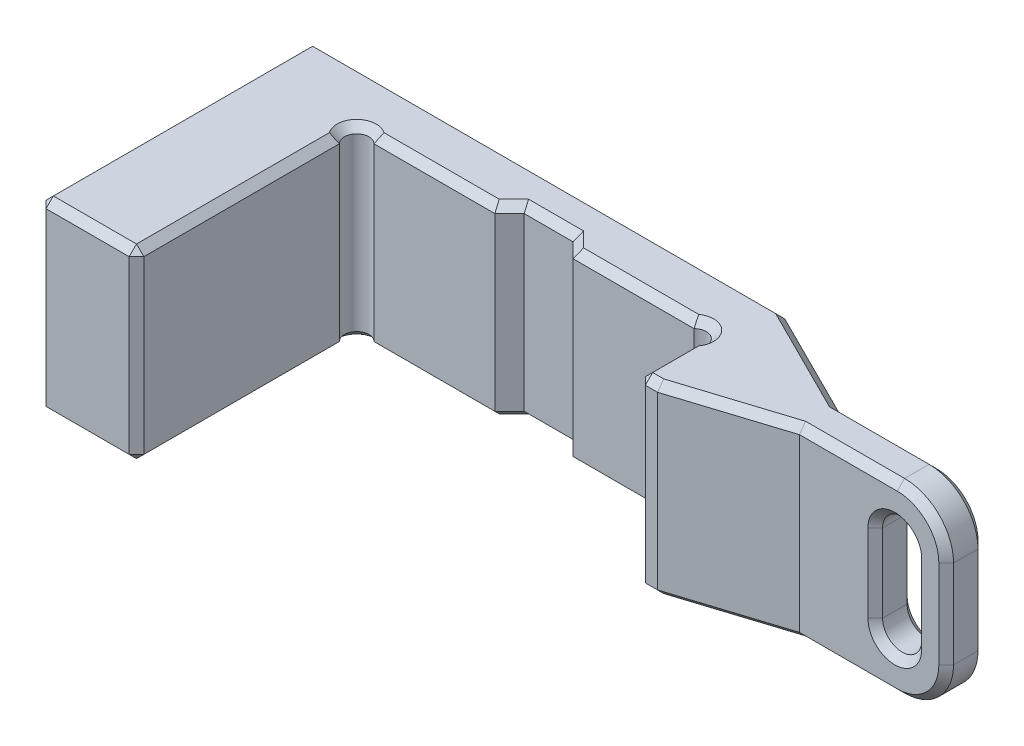
SolidWorks part; units mm, degrees
material "PET"
ref_plane "Front Plane" through (0, 0, 0) normal (0, 0, 1) x (1, 0, 0)
ref_plane "Top Plane" through (0, 0, 0) normal (0, 1, 0) x (1, 0, 0)
ref_plane "Right Plane" through (0, 0, 0) normal (1, 0, 0) x (0, 0, -1)
sketch "Sketch1" plane through (0, 0, 0) normal (0, 1, 0) x (1, 0, 0)
  line L0 (0, 0) -> (0, 56)
  line L1 (0, 56) -> (96.5, 56)
  line L2 (96.5, 56) -> (118.5, 45)
  line L3 (118.5, 45) -> (148.5, 45)
  line L4 (148.5, 45) -> (148.5, 37)
  line L5 (148.5, 37) -> (118.5, 37)
  line L11 (20, 41.4645) -> (20, 0)
  line L12 (20, 0) -> (0, 0)
  line L13 (118.5, 37) -> (96.5, 30)
  line L14 (96.5, 30) -> (92.5, 30)
  line L15 (92.5, 30) -> (92.5, 41.4645)
  line L17 (23.5355, 45) -> (48.25, 45)
  line L18 (48.25, 45) -> (51.25, 48)
  line L19 (51.25, 48) -> (61.25, 48)
  line L20 (61.25, 48) -> (64.25, 45)
  line L21 (64.25, 45) -> (88.9645, 45)
  line L22 (20, 41.4645) -> (23.5355, 45) construction
  line L23 (88.9645, 45) -> (92.5, 41.4645) construction
  arc A0 (20, 41.4645) -> (23.5355, 45) centre (21.7678, 43.2322) cw
  arc A1 (88.9645, 45) -> (92.5, 41.4645) centre (90.7322, 43.2322) cw
  dimension "D14" = 2.5
  dimension "D15" = 2.5
  dimension "D2" = 20
  dimension "D3" = 72.5
  dimension "D4" = 10
  dimension "D5" = 3
  dimension "D6" = 11
  dimension "D7" = 4
  dimension "D8" = 26
  dimension "D9" = 30
  dimension "D10" = 45
  dimension "D11" = 8
  dimension "D12" = 135
  dimension "D13" = 135
  dimension "D16" = 15
extrude "Create profile" add sketch "Sketch1" along normal blind 38
sketch "Sketch3" plane through (0, 0, -45) normal (0, 0, -1) x (-1, 0, 0)
  line L0 (-138, 27) -> (-138, 11) construction
  line L1 (-134, 27) -> (-134, 11)
  line L2 (-142, 27) -> (-142, 11)
  line L3 (-148.5, 38) -> (-148.5, 0) construction
  arc A0 (-134, 27) -> (-142, 27) centre (-138, 27) ccw
  arc A1 (-142, 11) -> (-134, 11) centre (-138, 11) ccw
  point P2 (-138, 19)
  point P7 (0, 0)
  point P10 (-148.5, 19)
  point P11 (0, 0)
  dimension "D1" = 8
  dimension "16" = 16
  dimension "D2" = 6.5
extrude "Cut shackle hole" cut sketch "Sketch3" against normal through all
fillet "Round Edges" radius 10 2 edges at (148.5, 0, -41) (148.5, 38, -41)
chamfer "Unecessary chamfers" distance 1.5 angle 45 52 edges at (148.5, 19, -37) (148.5, 19, -45) (145.5711, 2.9289, -45) (145.5711, 2.9289, -37) (145.5711, 35.0711, -37) (145.5711, 35.0711, -45) (128.5, 0, -45) (107.5, 0, -50.5) (48.25, 0, -56) (0, 0, -28) (10, 0, 0) (20, 0, -20.7322) (20, 0, -45) (35.8928, 0, -45) (49.75, 0, -46.5) (56.25, 0, -48) (62.75, 0, -46.5) (76.6072, 0, -45) (92.5, 0, -45) (92.5, 0, -35.7322) (128.5, 0, -37) (107.5, 0, -33.5) (94.5, 0, -30) (128.5, 38, -37) (107.5, 38, -33.5) (94.5, 38, -30) (92.5, 19, -30) (92.5, 38, -35.7322) (92.5, 38, -45) (76.6072, 38, -45) (62.75, 38, -46.5) (56.25, 38, -48) (49.75, 38, -46.5) (35.8928, 38, -45) (20, 38, -45) (20, 38, -20.7322) (20, 19, 0) (10, 38, 0) (0, 19, 0) (0, 38, -28) (128.5, 38, -45) (107.5, 38, -50.5) (48.25, 38, -56) (0, 19, -56) (138, 31, -45) (142, 19, -45) (134, 19, -45) (138, 7, -45) (142, 19, -37) (138, 7, -37) (138, 31, -37) (134, 19, -37)
